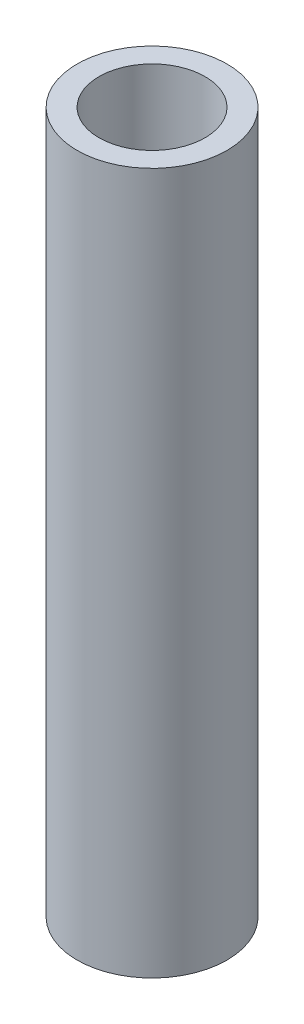
SolidWorks part; units mm, degrees
material "Rubber"
ref_plane "Front Plane" through (0, 0, 0) normal (0, 0, 1) x (1, 0, 0)
ref_plane "Top Plane" through (0, 0, 0) normal (0, 1, 0) x (1, 0, 0)
ref_plane "Right Plane" through (0, 0, 0) normal (1, 0, 0) x (0, 0, -1)
sketch "Sketch1" plane through (0, 0, 0) normal (0, 1, 0) x (1, 0, 0)
  circle A0 centre (0, 0) radius 6.05
extrude "Extrude-Thin1" add sketch "Sketch1" along normal blind 80 thin
